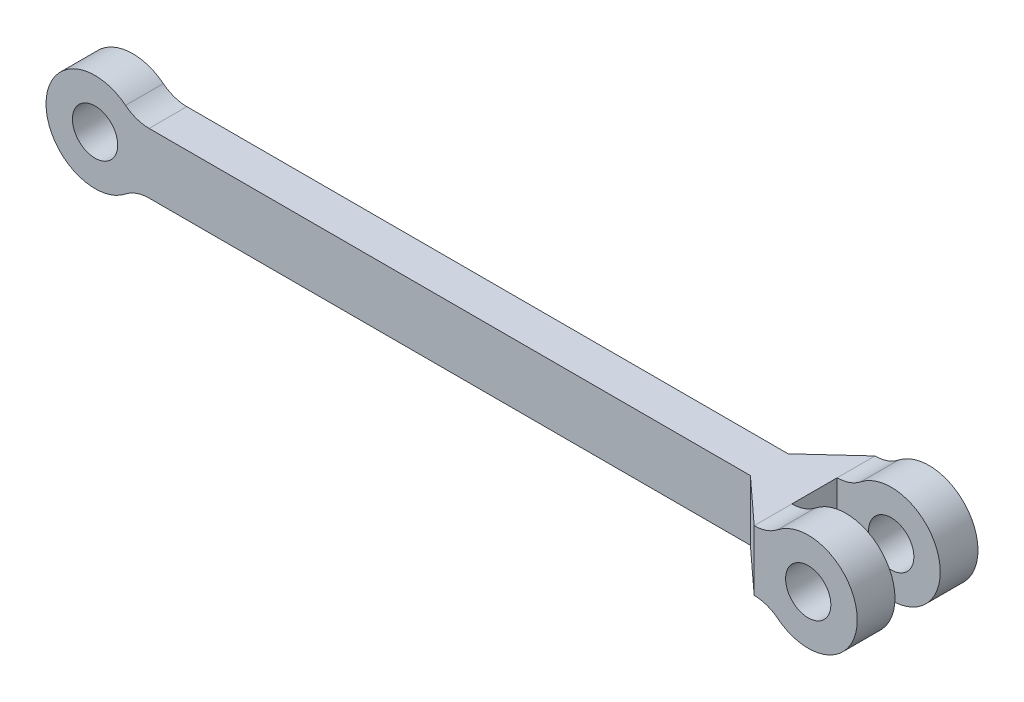
SolidWorks part; units mm, degrees
ref_plane "Front Plane" through (0, 0, 0) normal (0, 0, 1) x (1, 0, 0)
ref_plane "Top Plane" through (0, 0, 0) normal (0, 1, 0) x (1, 0, 0)
ref_plane "Right Plane" through (0, 0, 0) normal (1, 0, 0) x (0, 0, -1)
sketch "Sketch1" plane through (0, 0, 0) normal (0, 0, 1) x (1, 0, 0)
  line L0 (0, 0) -> (1000, 0) construction
  line L1 (71.5891, 40) -> (928.4109, 40)
  line L2 (71.5891, -40) -> (928.4109, -40)
  circle A0 centre (0, 0) radius 30
  circle A1 centre (1000, 0) radius 30
  arc A2 (40.4634, 50.8696) -> (40.4634, -50.8696) centre (0, 0) ccw
  arc A3 (959.5366, -50.8696) -> (959.5366, 50.8696) centre (1000, 0) ccw
  arc A4 (928.4109, -40) -> (959.5366, -50.8696) centre (928.4109, -90) cw
  arc A5 (928.4109, 40) -> (959.5366, 50.8696) centre (928.4109, 90) ccw
  arc A6 (71.5891, -40) -> (40.4634, -50.8696) centre (71.5891, -90) ccw
  arc A7 (71.5891, 40) -> (40.4634, 50.8696) centre (71.5891, 90) cw
  point P3 (500, 0)
  point P18 (51.2348, -40)
  point P21 (51.2348, 40)
  dimension "D3" = 130
  dimension "D4" = 60
  dimension "D5" = 50
  dimension "D1" = 1000
  dimension "D2" = 80
extrude "Boss-Extrude1" add sketch "Sketch1" along normal mid plane 50
sketch "Sketch3" plane through (0, 0, 0) normal (0, 0, 1) x (1, 0, 0)
  line L0 (71.5891, -40) -> (928.4109, -40) construction
  line L1 (928.4109, 40) -> (71.5891, 40) construction
  line L2 (868.4109, -40) -> (928.4109, -40)
  line L3 (928.4109, 40) -> (868.4109, 40)
  line L4 (868.4109, 40) -> (868.4109, -40)
  arc A0 (959.5366, -50.8696) -> (928.4109, -40) centre (928.4109, -90) ccw construction
  arc A1 (959.5366, -50.8696) -> (959.5366, 50.8696) centre (1000, 0) ccw construction
  arc A2 (928.4109, 40) -> (959.5366, 50.8696) centre (928.4109, 90) ccw construction
  arc A3 (959.5366, -50.8696) -> (928.4109, -40) centre (928.4109, -90) ccw
  arc A4 (959.5366, -50.8696) -> (959.5366, 50.8696) centre (1000, 0) ccw
  arc A5 (928.4109, 40) -> (959.5366, 50.8696) centre (928.4109, 90) ccw
  circle A6 centre (1000, 0) radius 30 construction
  circle A7 centre (1000, 0) radius 30
  dimension "D1" = 60
extrude "Boss-Extrude2" add sketch "Sketch3" along normal mid plane 160
sketch "Sketch4" plane through (0, 40, 0) normal (0, 1, 0) x (1, 0, 0)
  line L0 (868.4109, 25) -> (928.4109, 80)
  line L1 (928.4109, 80) -> (868.4109, 80)
  line L2 (868.4109, 80) -> (868.4109, 25)
  line L3 (1065, 30) -> (928.4109, 30)
  line L4 (928.4109, -80) -> (928.4109, 80) construction
  line L5 (928.4109, 30) -> (928.4109, -30)
  line L6 (928.4109, -30) -> (1065, -30)
  line L7 (1065, -30) -> (1065, 30)
  line L8 (1065, -80) -> (1065, 80) construction
  line L9 (1065, 0) -> (868.4109, 0) construction
  line L10 (928.4109, -80) -> (868.4109, -80)
  line L11 (868.4109, -25) -> (928.4109, -80)
  line L12 (868.4109, -80) -> (868.4109, -25)
  point P10 (1065, 0)
  point P13 (0, 0)
  dimension "D1" = 60
extrude "Cut-Extrude1" cut sketch "Sketch4" against normal through all both and the other way through all
